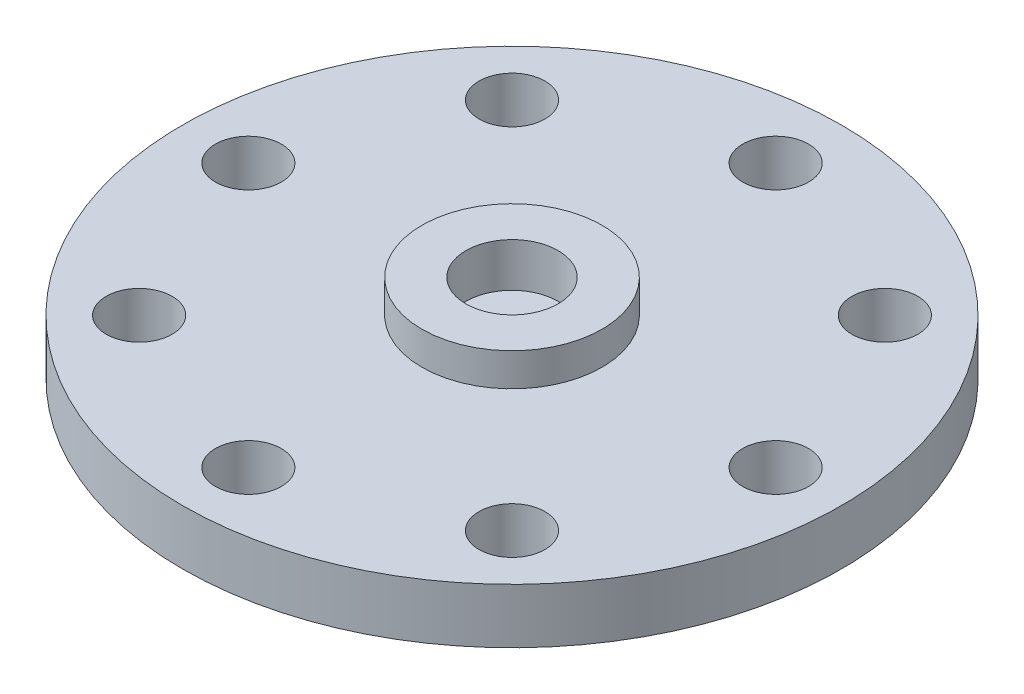
SolidWorks part; units mm, degrees
ref_plane "Front Plane" through (0, 0, 0) normal (0, 0, 1) x (1, 0, 0)
ref_plane "Top Plane" through (0, 0, 0) normal (0, 1, 0) x (1, 0, 0)
ref_plane "Right Plane" through (0, 0, 0) normal (1, 0, 0) x (0, 0, -1)
sketch "Sketch1" plane through (0, 0, 0) normal (0, 1, 0) x (1, 0, 0)
  circle A0 centre (-8.4457, 3.8168) radius 15
  circle A1 centre (-8.4457, 15.8168) radius 1.5
  circle A2 centre (0.0396, 12.3021) radius 1.5
  circle A3 centre (3.5543, 3.8168) radius 1.5
  circle A4 centre (0.0396, -4.6685) radius 1.5
  circle A5 centre (-8.4457, -8.1832) radius 1.5
  circle A6 centre (-16.931, -4.6685) radius 1.5
  circle A7 centre (-20.4457, 3.8168) radius 1.5
  circle A8 centre (-16.931, 12.3021) radius 1.5
  point P21 (-8.4457, 3.8168)
  dimension "D1" = 30
  dimension "D2" = 12
  dimension "D3" = 3
  dimension "D4" = 8
extrude "Boss-Extrude1" add sketch "Sketch1" along normal blind 4
sketch "Sketch2" plane through (0, 4, 0) normal (0, 1, 0) x (1, 0, 0)
  circle A0 centre (-8.4457, 3.8168) radius 2.1
  dimension "D1" = 4.2
extrude "Cut-Extrude1" cut sketch "Sketch2" against normal blind 2
sketch "Sketch3" plane through (0, 4, 0) normal (0, 1, 0) x (1, 0, 0)
  circle A0 centre (-8.4457, 3.8168) radius 4.1
  circle A1 centre (-8.4457, 3.8168) radius 2.1 construction
  circle A2 centre (-8.4457, 3.8168) radius 21.629
  dimension "D1" = 2
extrude "Cut-Extrude2" cut sketch "Sketch3" against normal blind 1.5
